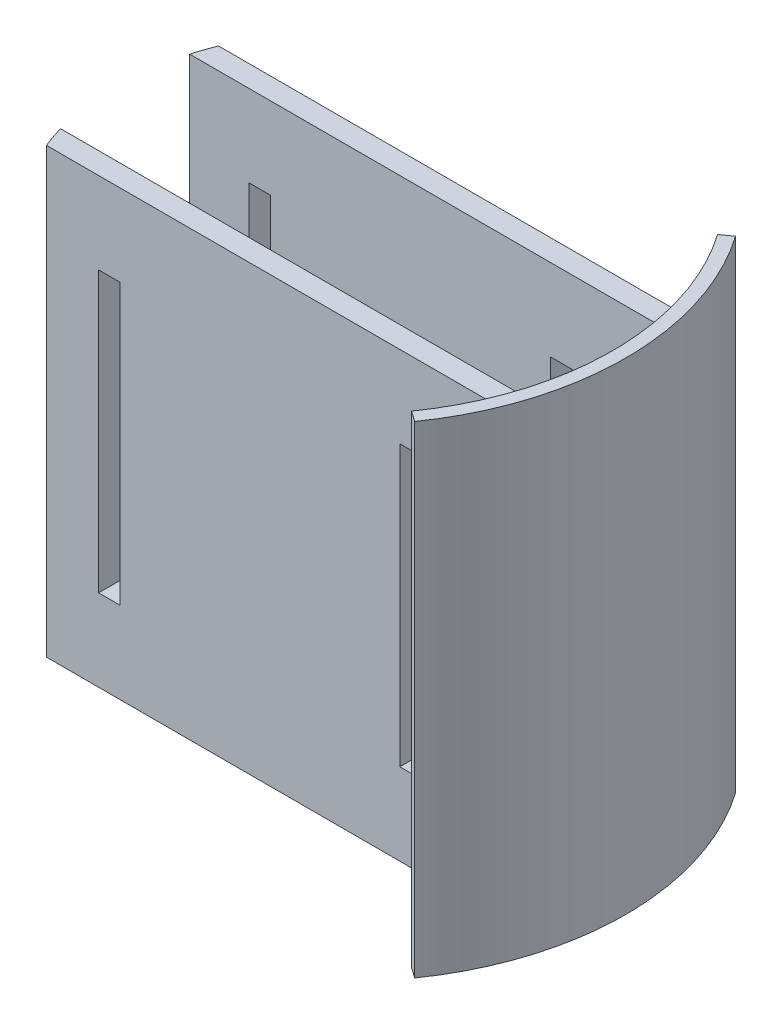
SolidWorks part; units mm, degrees
ref_plane "Front Plane" through (0, 0, 0) normal (0, 0, 1) x (1, 0, 0)
ref_plane "Top Plane" through (0, 0, 0) normal (0, 1, 0) x (1, 0, 0)
ref_plane "Right Plane" through (0, 0, 0) normal (1, 0, 0) x (0, 0, -1)
sketch "Sketch1" plane through (0, 0, 0) normal (0, 1, 0) x (1, 0, 0)
  line L0 (50.7874, 35.5617) -> (53.2449, 37.2825)
  line L1 (-71.5, 0) -> (71.5, 0) construction
  line L2 (50.7874, -35.5617) -> (53.2449, -37.2825)
  line L3 (0, 0) -> (50.7874, 35.5617) construction
  line L4 (0, 0) -> (50.7874, -35.5617) construction
  arc A0 (53.2449, -37.2825) -> (53.2449, 37.2825) centre (0, 0) ccw
  arc A1 (50.7874, -35.5617) -> (50.7874, 35.5617) centre (0, 0) ccw
  dimension "D1" = 130
  dimension "D2" = 124
  dimension "D3" = 70
extrude "Boss-Extrude1" add sketch "Sketch1" along normal mid plane 112
sketch "Sketch2" plane through (0, 0, 0) normal (0, 1, 0) x (1, 0, 0)
  line L0 (-51.3542, 15) -> (60.1581, 15)
  line L1 (-49.6211, 20) -> (58.6856, 20)
  line L2 (-61.6, 0) -> (61.6, 0) construction
  line L3 (-49.6211, -20) -> (58.6856, -20)
  line L4 (-51.3542, -15) -> (60.1581, -15)
  arc A0 (-49.6211, 20) -> (-51.3542, 15) centre (0, 0) ccw
  arc A1 (50.7874, -35.5617) -> (50.7874, 35.5617) centre (0, 0) ccw construction
  arc A2 (-49.6211, -20) -> (-51.3542, -15) centre (0, 0) cw
  arc A3 (58.6856, -20) -> (60.1581, -15) centre (0, 0) ccw
  arc A4 (60.1581, 15) -> (58.6856, 20) centre (0, 0) ccw
  dimension "D1" = 30
  dimension "D3" = 53.5
  dimension "D2" = 40
extrude "Boss-Extrude2" add sketch "Sketch2" along normal mid plane 103
sketch "Sketch3" plane through (0, 0, 20) normal (0, 0, 1) x (1, 0, 0)
  line L0 (41.0107, 0) -> (-41.0107, 0) construction
  line L1 (-37.5, -32.5) -> (-32.5, -32.5)
  line L2 (-37.5, -32.5) -> (-37.5, 32.5)
  line L3 (-37.5, 32.5) -> (-32.5, 32.5)
  line L4 (-32.5, -32.5) -> (-32.5, 32.5)
  line L5 (-37.5, -32.5) -> (-32.5, 32.5) construction
  line L6 (-37.5, 32.5) -> (-32.5, -32.5) construction
  line L7 (0, -41.0107) -> (0, 41.0107) construction
  line L8 (37.5, 32.5) -> (32.5, -32.5) construction
  line L9 (37.5, -32.5) -> (32.5, 32.5) construction
  line L10 (32.5, -32.5) -> (32.5, 32.5)
  line L11 (37.5, 32.5) -> (32.5, 32.5)
  line L12 (37.5, -32.5) -> (37.5, 32.5)
  line L13 (37.5, -32.5) -> (32.5, -32.5)
  point P0 (-35, 0)
  point P13 (35, 0)
  dimension "D1" = 65
  dimension "D2" = 5
  dimension "D3" = 65
extrude "Cut-Extrude1" cut sketch "Sketch3" against normal up to surface (40 mm away) up to face at (4.5323, 0, -20)
